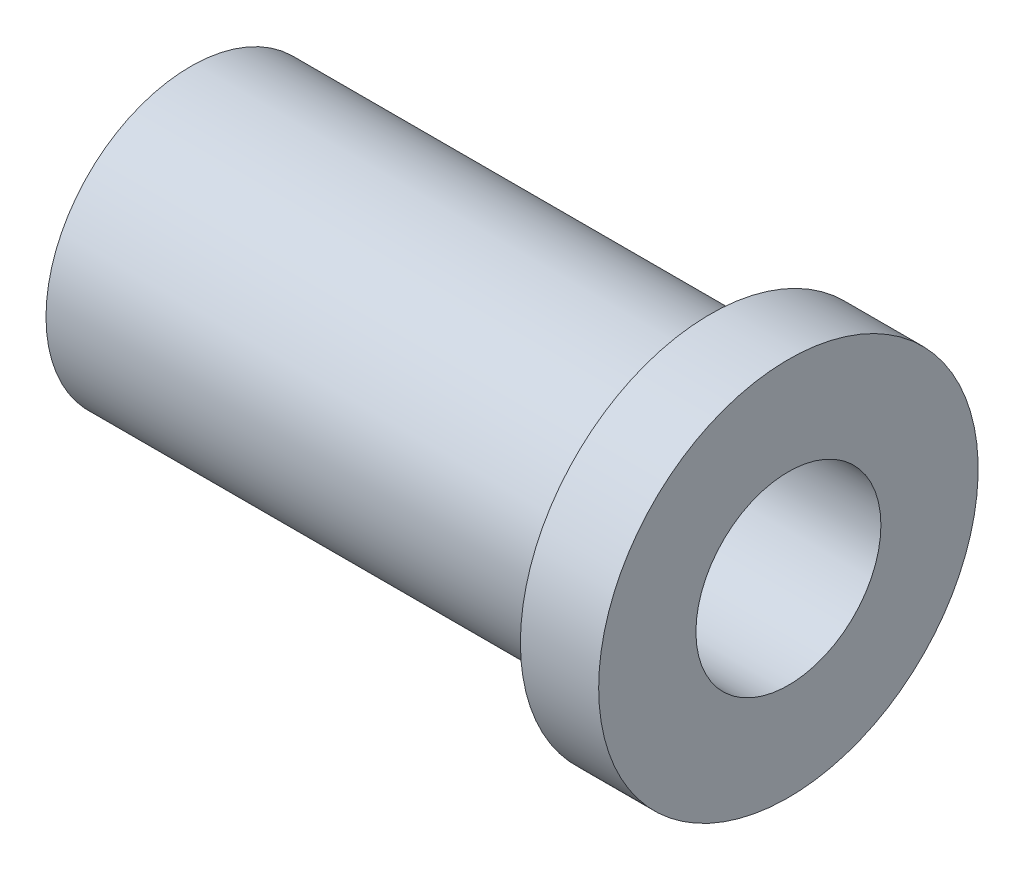
SolidWorks part; units mm, degrees
ref_plane "Piano frontale" through (0, 0, 0) normal (0, 0, 1) x (1, 0, 0)
ref_plane "Piano superiore" through (0, 0, 0) normal (0, 1, 0) x (1, 0, 0)
ref_plane "Piano destro" through (0, 0, 0) normal (1, 0, 0) x (0, 0, -1)
sketch "Schizzo1" plane through (0, 0, 0) normal (0, 1, 0) x (1, 0, 0)
  line L0 (-60.4997, 0) -> (58.3272, 0) construction
  line L1 (0, 3.9) -> (0, 6.1)
  line L2 (0, 6.1) -> (21.7, 6.1)
  line L3 (21.9, 6.3) -> (21.9, 8)
  line L4 (21.9, 8) -> (25.2, 8)
  line L5 (25.2, 8) -> (25.2, 3.9)
  line L6 (25.2, 3.9) -> (0, 3.9)
  arc A0 (21.7, 6.1) -> (21.9, 6.3) centre (21.7, 6.3) ccw
  dimension "D6" = 0.2
  dimension "D1" = 25.2
  dimension "D2" = 21.9
  dimension "D3" = 16
  dimension "D4" = 12.2
  dimension "D5" = 7.8
revolve "Rivoluzione1" add sketch "Schizzo1" angle 360 about L0
sketch "Schizzo2" plane through (0, 0, 0) normal (0, 1, 0) x (1, 0, 0)
  line L1 (0, -6.1) -> (21.7, -6.1) construction
  line L2 (20.1, -5.9) -> (21.7, -5.9)
  line L3 (21.9, -6.1) -> (21.9, -6.2903)
  line L4 (21.9, -6.2903) -> (19.9, -6.1)
  line L5 (21.9, 8) -> (21.9, -8) construction
  line L6 (-5.6488, 0) -> (30.1726, 0) construction
  arc A0 (21.7, -5.9) -> (21.9, -6.1) centre (21.7, -6.1) cw
  arc A1 (20.1, -5.9) -> (19.9, -6.1) centre (20.1, -6.1) ccw
  dimension "D3" = 0.2
  dimension "D4" = 0.2
  dimension "D1" = 0.2
  dimension "D2" = 2
